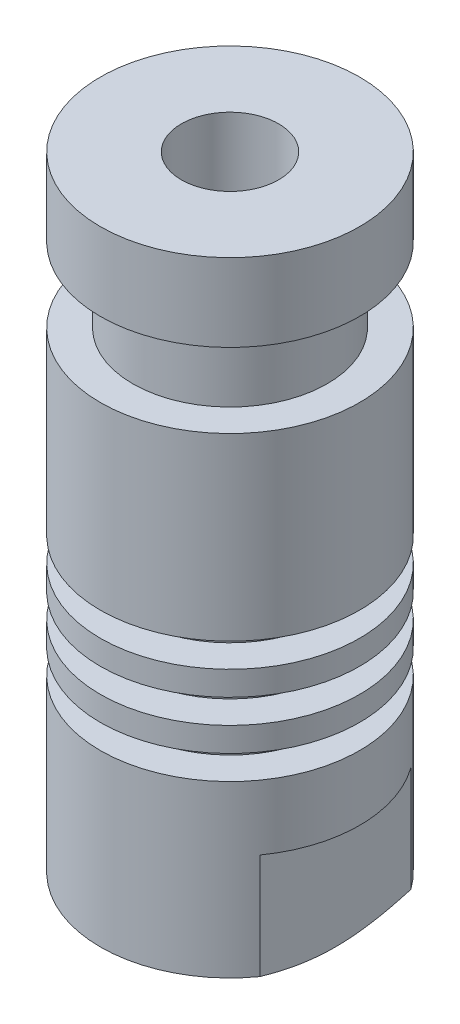
SolidWorks part; units mm, degrees
material "Gomma"
ref_plane "Piano frontale" through (0, 0, 0) normal (0, 0, 1) x (1, 0, 0)
ref_plane "Piano superiore" through (0, 0, 0) normal (0, 1, 0) x (1, 0, 0)
ref_plane "Piano destro" through (0, 0, 0) normal (1, 0, 0) x (0, 0, -1)
sketch "Schizzo1" plane through (0, 0, 0) normal (0, 0, 1) x (1, 0, 0)
  line L0 (0, 0) -> (-5, 0)
  line L1 (-5, 0) -> (-8, 1.5)
  line L2 (-8, 1.5) -> (-8, 12)
  line L3 (-8, 12) -> (-6, 12)
  line L4 (-6, 12) -> (-6, 13.5)
  line L5 (-6, 13.5) -> (-8, 13.5)
  line L6 (-8, 13.5) -> (-8, 15)
  line L7 (-8, 15) -> (-6, 15)
  line L8 (-6, 15) -> (-6, 16.5)
  line L9 (-6, 16.5) -> (-8, 16.5)
  line L10 (-8, 16.5) -> (-8, 18)
  line L11 (-8, 18) -> (-6, 18)
  line L12 (-6, 18) -> (-6, 19.5)
  line L13 (-6, 19.5) -> (-8, 19.5)
  line L14 (-8, 19.5) -> (-8, 30.6)
  line L15 (-8, 30.6) -> (-6, 30.6)
  line L16 (-6, 30.6) -> (-6, 35.2)
  line L17 (-6, 35.2) -> (-8, 35.2)
  line L18 (-8, 35.2) -> (-8, 40)
  line L19 (-8, 40) -> (0, 40)
  line L20 (0, 40) -> (0, 0)
  line L21 (0, 129.4074) -> (0, -17.2322) construction
  dimension "D1" = 1.5
  dimension "D2" = 16
  dimension "D3" = 2
  dimension "D4" = 40
  dimension "D5" = 12
  dimension "D6" = 4.8
  dimension "D7" = 4.6
  dimension "D8" = 1.5
  dimension "D9" = 6
  dimension "D10" = 10
  dimension "D11" = 12
  dimension "D12" = 1.5
  dimension "D13" = 1.5
revolve "Rivoluzione1" add sketch "Schizzo1" angle 360 about L21
sketch "Schizzo2" plane through (0, 0, 0) normal (0, 0, 1) x (1, 0, 0)
  line L0 (-8, 8) -> (-6.5, 8)
  line L1 (-6.5, 8) -> (-6.5, 0)
  line L2 (-6.5, 0) -> (-8, 0)
  line L3 (-8, 0) -> (-8, 8)
  line L4 (6.5, 8) -> (6.5, 0)
  line L5 (6.5, 0) -> (8, 0)
  line L6 (8, 0) -> (8, 8)
  line L7 (8, 8) -> (6.5, 8)
  line L8 (0, 0) -> (0, 9.0399) construction
  line L9 (-5, 0) -> (5, 0) construction
  line L10 (8, 40) -> (-8, 40) construction
  line L11 (8, 1.5) -> (8, 12) construction
  line L12 (-8, 12) -> (-8, 1.5) construction
  dimension "D1" = 32
  dimension "D2" = 1.5
extrude "Taglio-Estrusione1" cut sketch "Schizzo2" against normal up to next and the other way up to next
sketch "Schizzo7" plane through (0, 40, 0) normal (0, 1, 0) x (1, 0, 0)
  circle A0 centre (0, 0) radius 3
extrude "Taglio-Estrusione2" cut sketch "Schizzo7" against normal through all
hole_wizard "Foro filettato M8-1" positions "Schizzo9" profile "Schizzo8" tap size "M8" standard "ISO"
sketch "Schizzo9" plane through (0, 0, 0) normal (0, -1, 0) x (-1, 0, 0)
  point P0 (0, 0)
sketch "Schizzo8" plane through (0, 0, 0) normal (1, 0, 0) x (0, 0, -1)
  line L0 (0, 0) -> (0, 14.0429)
  line L1 (0, 14.0429) -> (3.4, 12)
  line L2 (3.4, 12) -> (3.4, 0)
  line L5 (3.4, 0) -> (0, 0)
  line L10 (0, 14.0429) -> (-3.4, 12) construction
  line L11 (0, -6.35) -> (0, 107.95) construction
  dimension "Tap Drill Dia." = 6.8
  dimension "Tap Drill Depth" = 12
  dimension "Drill Angle" = 118
cosmetic thread "Filettatura del foro3" parameters "D1"=12, "D2"=8
